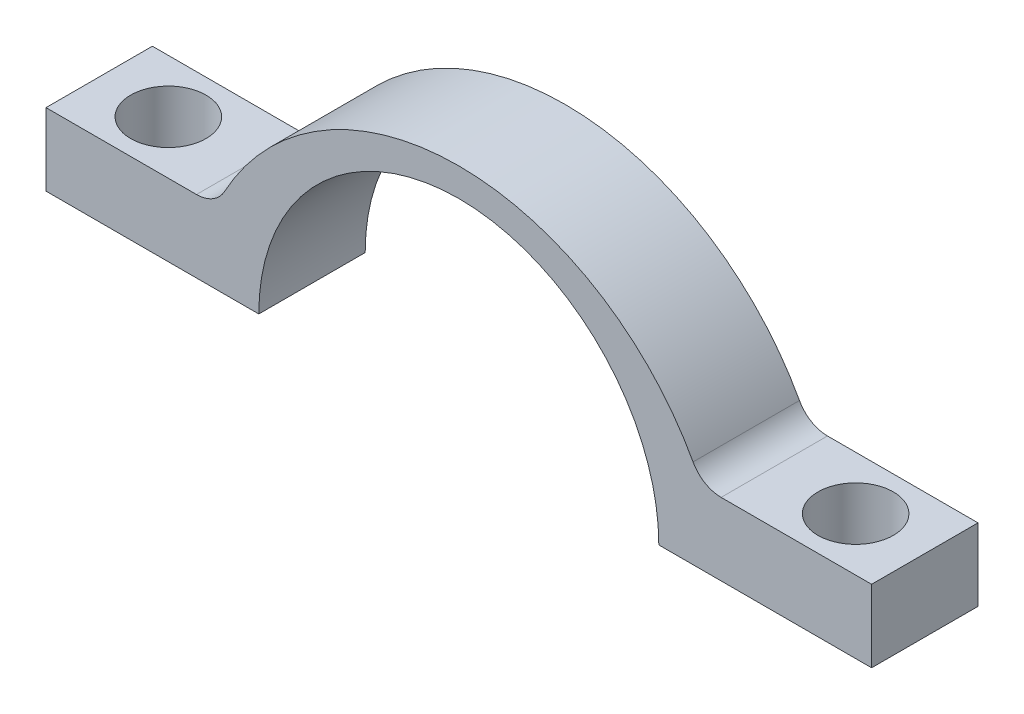
SolidWorks part; units mm, degrees
material "1060 Alloy"
ref_plane "Front Plane" through (0, 0, 0) normal (0, 0, 1) x (1, 0, 0)
ref_plane "Top Plane" through (0, 0, 0) normal (0, 1, 0) x (1, 0, 0)
ref_plane "Right Plane" through (0, 0, 0) normal (1, 0, 0) x (0, 0, -1)
sketch "Sketch1" plane through (0, 0, 0) normal (0, 0, 1) x (1, 0, 0)
  line L0 (0, 0) -> (-12.7, 0)
  line L1 (0, 0) -> (0, 4.318)
  line L2 (0, 4.318) -> (-10.16, 4.318)
  line L3 (-36.576, 0) -> (-49.276, 0)
  line L4 (-49.276, 0) -> (-49.276, 4.318)
  line L5 (-49.276, 4.318) -> (-39.116, 4.318)
  arc A0 (-36.576, 0) -> (-12.7, 0) centre (-24.638, 0) cw
  arc A3 (-39.116, 4.318) -> (-10.16, 4.318) centre (-24.638, -2.286) cw
  point P11 (0, 0)
  point P12 (0, 0)
  point P13 (-49.276, 0)
  point P14 (-12.7, 0)
  point P15 (-36.576, 0)
  point P18 (-15.3714, 0)
  dimension "D2" = 4.318
  dimension "D1" = 2.54
  dimension "D3" = 2.286
extrude "Boss-Extrude1" add sketch "Sketch1" along normal blind 6.35
sketch "Sketch2" plane through (0, 4.318, 0) normal (0, 1, 0) x (1, 0, 0)
  circle A2 centre (-4.1275, -3.175) radius 2.0828
  circle A3 centre (-4.1275, -3.175) radius 2.0828
  dimension "D1" = 0
hole_wizard "M4 Clearance Hole1" positions "Sketch4" profile "Sketch6" hole size "M4" standard "ANSI Metric" end condition through all
sketch "Sketch4" plane through (0, 4.318, 0) normal (0, 1, 0) x (1, 0, 0)
  point P0 (-4.1275, -3.175)
sketch "Sketch6" plane through (-4.1275, 4.318, 3.175) normal (1, 0, 0) x (0, 0, 1)
  line L0 (0, 0) -> (0, 4.318)
  line L1 (0, 4.318) -> (2.25, 4.318)
  line L2 (2.25, 4.318) -> (2.25, 0)
  line L5 (2.25, 0) -> (0, 0)
  line L11 (0, -6.35) -> (0, 107.95) construction
  dimension "Thru Hole Dia." = 4.5
  dimension "Thru Hole Depth" = 4.318
ref_plane "Plane1" through (-24.638, 11.938, 0) normal (1, 0, 0) x (0, 0, -1)
fillet "Fillet1" radius 1.905 2 edges at (-39.116, 4.318, 3.175) (-10.16, 4.318, 3.175)
sketch "Sketch3" plane through (-24.638, -11.938, 0) normal (-1, 0, 0) x (0, 0, 1)
  line L0 (6.35, 23.876) -> (0, 23.876)
  line L1 (6.35, 23.876) -> (0, 23.876)
split line "Split Line1"
ref_plane "Plane2" through (-24.638, 0, 0) normal (1, 0, 0) x (0, 0, -1)
mirror "Mirror1" about plane through (-24.638, 0, 0) normal (1, 0, 0) of "M4 Clearance Hole1"
